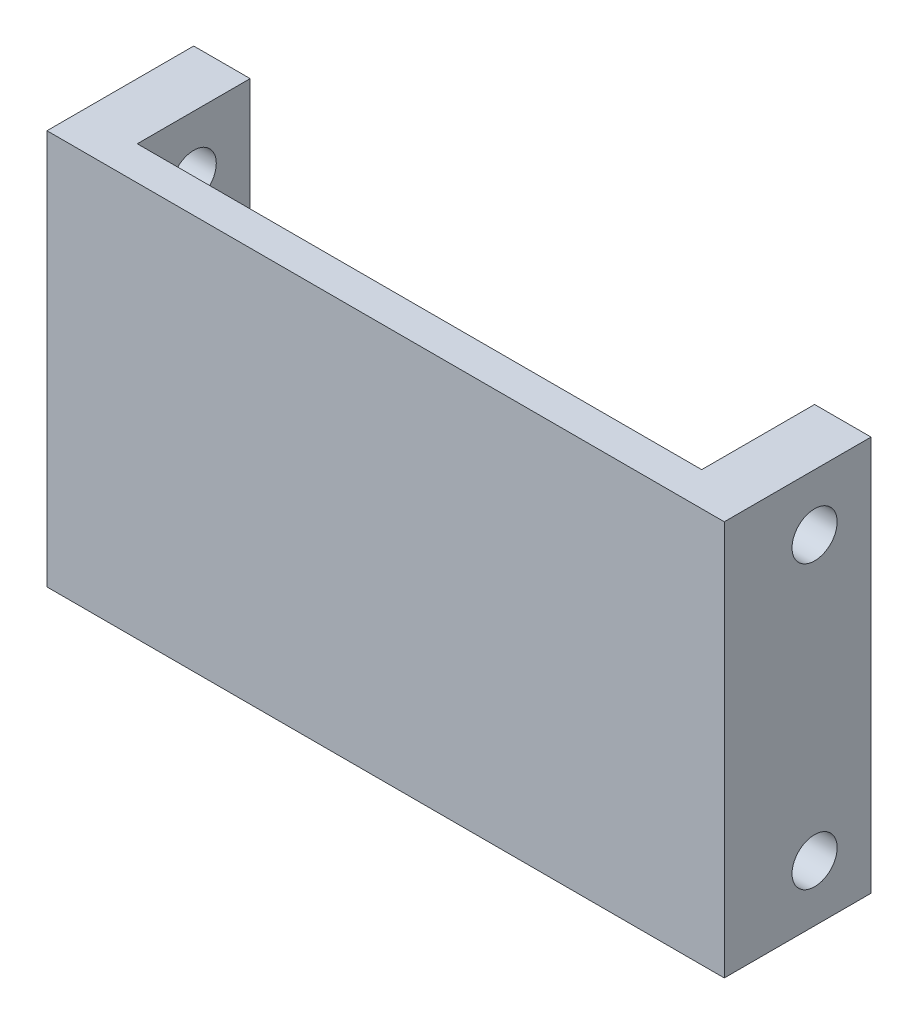
SolidWorks part; units mm, degrees
ref_plane "Front" through (0, 0, 0) normal (0, 0, 1) x (1, 0, 0)
ref_plane "Top" through (0, 0, 0) normal (0, 1, 0) x (1, 0, 0)
ref_plane "Right" through (0, 0, 0) normal (1, 0, 0) x (0, 0, -1)
sketch "Sketch2" plane through (0, 0, 0) normal (0, 0, 1) x (1, 0, 0)
  line L0 (-30, 17.5) -> (30, -17.5) construction
  line L1 (-30, 17.5) -> (30, 17.5)
  line L2 (-30, 17.5) -> (-30, -17.5)
  line L3 (-30, -17.5) -> (30, -17.5)
  line L4 (30, 17.5) -> (30, -17.5)
  line L5 (30, -17.5) -> (28.5552, -19.9768) construction
  dimension "D1" = 60
  dimension "D2" = 35
extrude "Boss-Extrude1" add sketch "Sketch2" along normal blind 3
sketch "Sketch3" plane through (0, 0, 0) normal (0, 0, -1) x (-1, 0, 0)
  line L0 (30, -17.5) -> (-30, -17.5) construction
  line L1 (-30, 17.5) -> (-25, 17.5)
  line L2 (-30, 17.5) -> (-30, -17.5)
  line L3 (-30, -17.5) -> (-25, -17.5)
  line L4 (-25, 17.5) -> (-25, -17.5)
  line L6 (30, 17.5) -> (25, 17.5)
  line L7 (30, 17.5) -> (30, -17.5)
  line L8 (30, -17.5) -> (25, -17.5)
  line L9 (25, 17.5) -> (25, -17.5)
  line M7 (30, -17.5) -> (30, 17.5)
  line M8 (30, 17.5) -> (-30, 17.5)
  line M9 (-30, 17.5) -> (-30, -17.5)
  line M10 (-30, -17.5) -> (30, -17.5)
  dimension "D1" = 5
  dimension "D2" = 5
extrude "Boss-Extrude2" add sketch "Sketch3" along normal blind 10 contours L4 M8 M9 M10 | L9 M8 M10 M7
sketch "Sketch4" plane through (30, 0, 0) normal (1, 0, 0) x (0, 0, -1)
  line L0 (5, 12.5) -> (5, -12.5) construction
  line L1 (-3, -17.5) -> (-3, 17.5) construction
  circle A0 centre (5, 12.5) radius 2
  circle A1 centre (5, -12.5) radius 2
  dimension "D1" = 4
  dimension "D2" = 25
  dimension "D3" = 8
extrude "Cut-Extrude1" cut sketch "Sketch4" against normal through all
